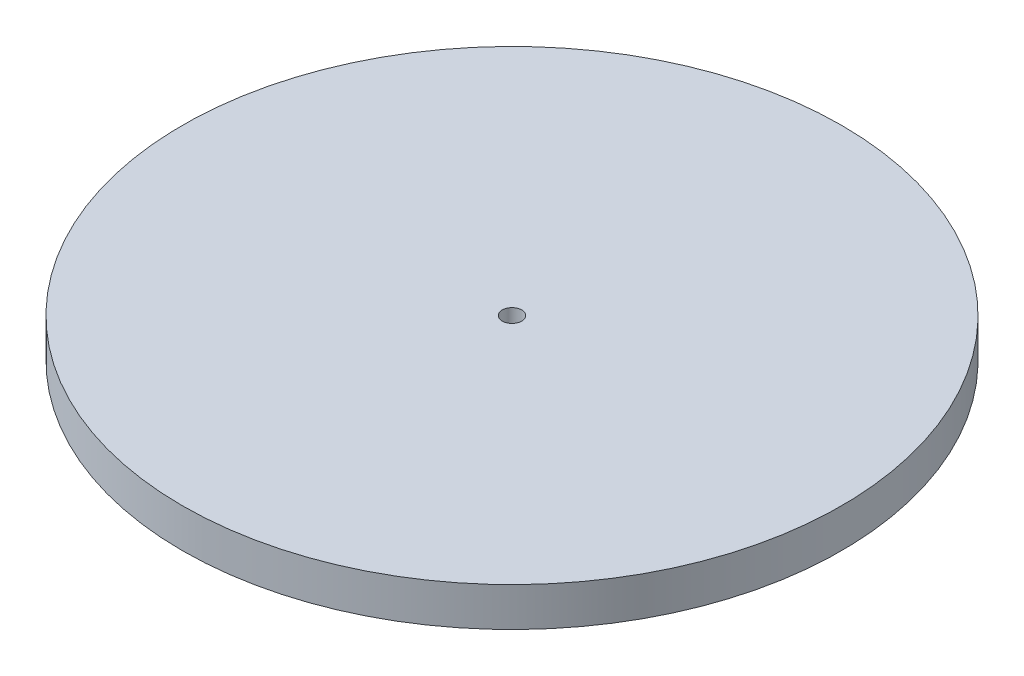
SolidWorks part; units mm, degrees
ref_plane "Front Plane" through (0, 0, 0) normal (0, 0, 1) x (1, 0, 0)
ref_plane "Top Plane" through (0, 0, 0) normal (0, 1, 0) x (1, 0, 0)
ref_plane "Right Plane" through (0, 0, 0) normal (1, 0, 0) x (0, 0, -1)
sketch "Sketch1" plane through (0, 0, 0) normal (0, 1, 0) x (1, 0, 0)
  circle A0 centre (0, 0) radius 25.4
  circle A1 centre (0, 0) radius 0.75
  dimension "D1" = 50.8
  dimension "D2" = 1.5
extrude "Boss-Extrude1" add sketch "Sketch1" along normal mid plane 3 contours A0
sketch "Sketch2" plane through (0, 1.5, 0) normal (0, 1, 0) x (1, 0, 0)
  circle A0 centre (0, 0) radius 0.75
  dimension "D1" = 1.5
extrude "Cut-Extrude1" cut sketch "Sketch2" against normal through all
